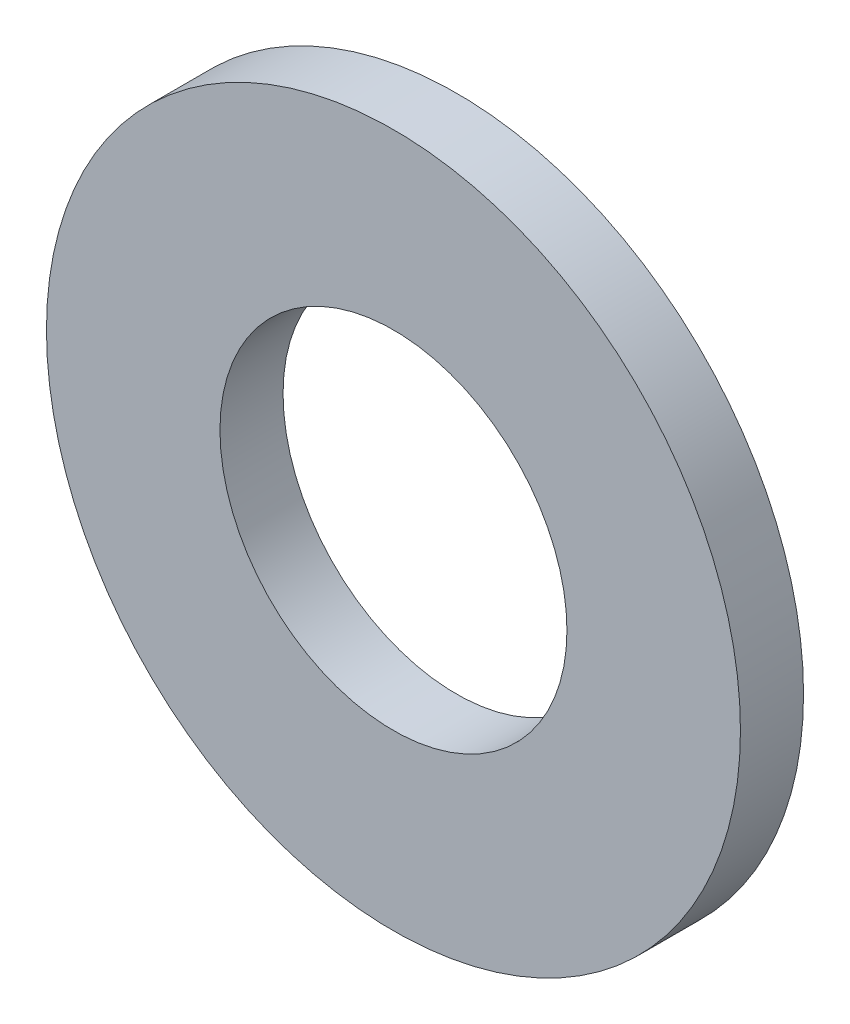
SolidWorks part; units mm, degrees
ref_plane "Front Plane" through (0, 0, 0) normal (1, 0, 0) x (0, 1, 0)
ref_plane "Top Plane" through (0, 0, 0) normal (0, 0, 1) x (0, 1, 0)
ref_plane "Right Plane" through (0, 0, 0) normal (0, 1, 0) x (-1, 0, 0)
sketch "Sketch1" plane through (0, 0, 0) normal (0, 0, 1) x (0, 1, 0)
  circle A0 centre (0, 0) radius 4.3656
  circle A1 centre (0, 0) radius 8.7312
  dimension "D1" = 8.7312
  dimension "D2" = 17.4625
extrude "Boss-Extrude1" add sketch "Sketch1" along normal blind 1.5875
